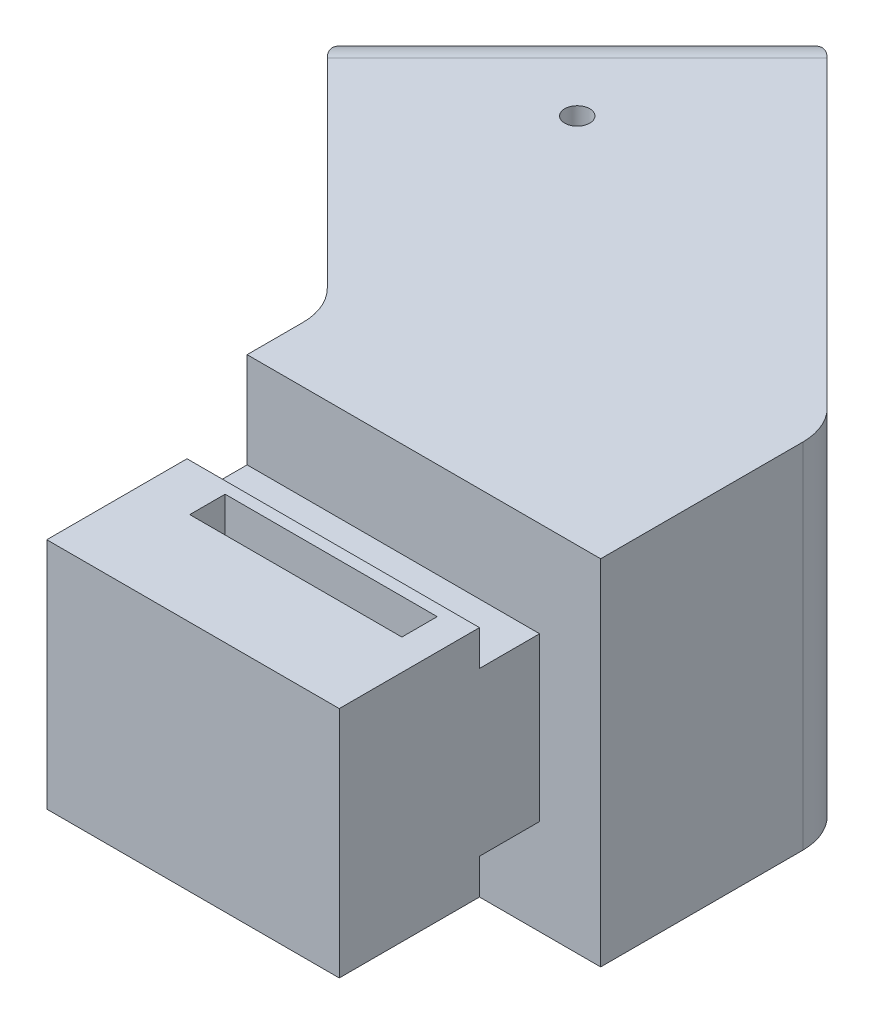
SolidWorks part; units mm, degrees
ref_plane "Front Plane" through (0, 0, 0) normal (0, 0, 1) x (1, 0, 0)
ref_plane "Top Plane" through (0, 0, 0) normal (0, 1, 0) x (1, 0, 0)
ref_plane "Right Plane" through (0, 0, 0) normal (1, 0, 0) x (0, 0, -1)
sketch "Sketch1" plane through (0, 0, 0) normal (0, 1, 0) x (1, 0, 0)
  line L0 (0, 0) -> (-31.5214, 0)
  line L1 (-31.5214, 0) -> (-31.5214, 30.226)
  line L3 (6.5786, 46.0075) -> (-31.5214, 84.1075)
  line L4 (-31.5214, 30.226) -> (-58.4622, 57.1668)
  line L5 (-58.4622, 57.1668) -> (-31.5214, 84.1075)
  line L6 (0, 0) -> (0, 21.59)
  line L7 (0, 21.59) -> (6.5786, 21.59)
  line L8 (6.5786, 21.59) -> (6.5786, 46.0075)
  dimension "D1" = 31.5214
  dimension "D2" = 38.1
  dimension "D3" = 38.1
  dimension "D4" = 38.1
  dimension "D5" = 30.226
  dimension "D6" = 21.59
  dimension "D7" = 225
extrude "Boss-Extrude1" add sketch "Sketch1" along normal blind 38.1
sketch "Sketch3" plane through (-31.5214, 0, 0) normal (-1, 0, 0) x (0, 0, 1)
  line L0 (-80.3357, 19.05) -> (-48.1795, 19.05) construction
  line L1 (0, 38.1) -> (0, 0) construction
  line L2 (-30.226, 0) -> (0, 0) construction
  line L3 (-21.59, 0) -> (-15.113, 0)
  line L4 (-21.59, 0) -> (-21.59, 10.287)
  line L5 (-21.59, 10.287) -> (-15.113, 10.287)
  line L6 (-15.113, 0) -> (-15.113, 10.287)
  line L7 (-21.59, 27.813) -> (-15.113, 27.813)
  line L8 (-15.113, 38.1) -> (-15.113, 27.813)
  line L9 (-21.59, 38.1) -> (-15.113, 38.1)
  line L10 (-21.59, 38.1) -> (-21.59, 27.813)
  line L11 (-15.113, 31.623) -> (0, 31.623)
  line L12 (-15.113, 0) -> (0, 0)
  line L13 (-15.113, 0) -> (-15.113, 6.477)
  line L14 (-15.113, 6.477) -> (0, 6.477)
  line L15 (0, 0) -> (0, 6.477)
  line L16 (0, 38.1) -> (0, 31.623)
  line L17 (-15.113, 38.1) -> (0, 38.1)
  line L18 (-15.113, 38.1) -> (-15.113, 31.623)
  point P4 (0, 19.05)
  line M10 (-30.226, 0) -> (0, 0)
  line M11 (0, 0) -> (0, 38.1)
  line M12 (0, 38.1) -> (-30.226, 38.1)
  dimension "D1" = 15.113
  dimension "D2" = 6.477
  dimension "D3" = 10.287
  dimension "D4" = 6.477
extrude "Cut-Extrude3" cut sketch "Sketch3" against normal through all contours L10 L7 L8 M12 | L8 L11 M11 M12 | L6 L5 L4 M10 | L14 L6 M10 M11
sketch "Sketch4" plane through (0, 6.477, 0) normal (0, -1, 0) x (1, 0, 0)
  line L0 (0, 0) -> (-31.5214, 0) construction
  line L1 (-26.162, -10.0482) -> (-3.302, -10.0482)
  line L2 (-26.162, -10.0482) -> (-26.162, -13.8582)
  line L3 (-26.162, -13.8582) -> (-3.302, -13.8582)
  line L4 (-3.302, -10.0482) -> (-3.302, -13.8582)
  line L5 (0, -15.113) -> (0, 0) construction
  dimension "D1" = 3.81
  dimension "D2" = 10.0482
  dimension "D3" = 22.86
  dimension "D4" = 3.302
extrude "Cut-Extrude4" cut sketch "Sketch4" against normal through all
sketch "Sketch5" plane through (-57.8145, 0, -57.8145) normal (-0.7071, 0, -0.7071) x (-0.7071, 0, 0.7071)
  line L0 (-37.184, 38.1) -> (-37.184, 0) construction
  line L1 (-37.184, 38.1) -> (0.916, 38.1) construction
  circle A0 centre (-18.134, 19.05) radius 10.8585
  point P4 (-37.184, 19.05)
  point P7 (-18.134, 38.1)
  dimension "D1" = 21.717
extrude "Cut-Extrude5" cut sketch "Sketch5" against normal blind 25.4
fillet "Fillet1" radius 6.35 2 edges at (6.5786, 19.05, -46.0075) (-31.5214, 19.05, -30.226)
sketch "Sketch6" plane through (0, 38.1, 0) normal (0, 1, 0) x (1, 0, 0)
  line L0 (-31.5214, 84.1075) -> (-58.4622, 57.1668) construction
  line L1 (-44.9918, 70.6372) -> (-36.0115, 61.6569) construction
  circle A0 centre (-36.0115, 61.6569) radius 1.35
  dimension "D2" = 2.7
  dimension "D1" = 12.7
extrude "Cut-Extrude6" cut sketch "Sketch6" against normal through all both and the other way through all
fillet "Fillet2" radius 5.08 4 edges at (-44.9918, 0, -70.6372) (-31.5214, 19.05, -84.1075) (-44.9918, 38.1, -70.6372) (-58.4622, 19.05, -57.1668)
